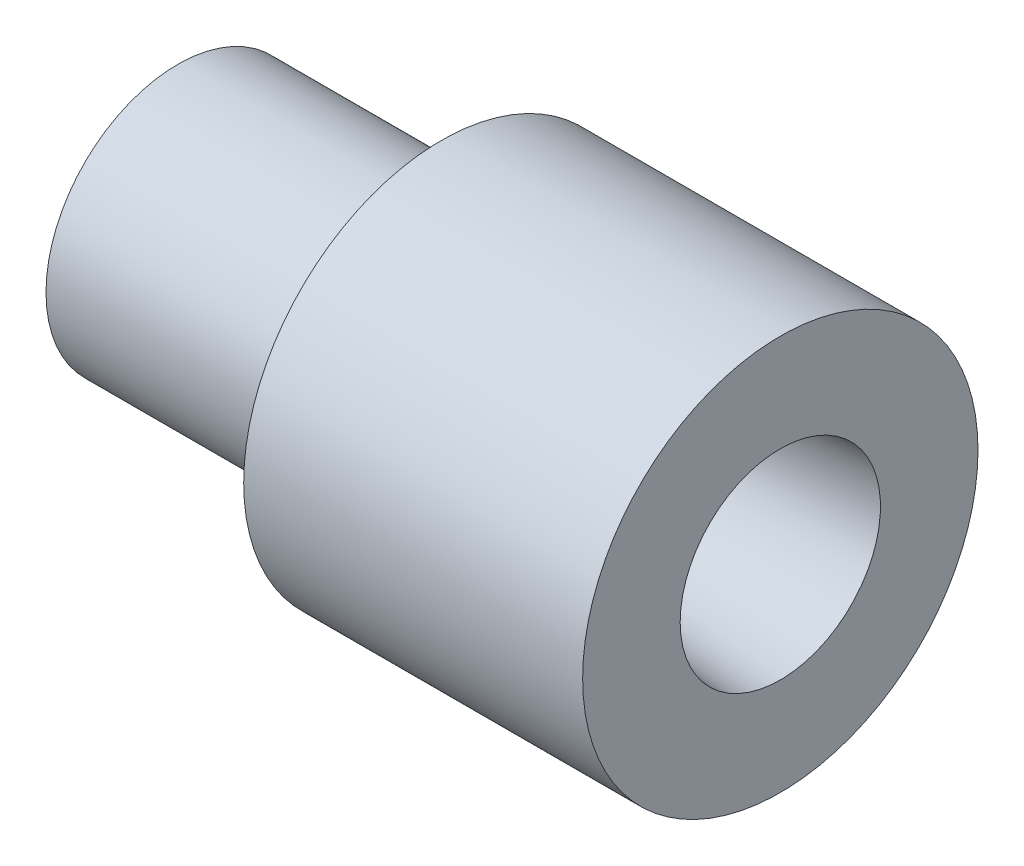
SolidWorks part; units mm, degrees
ref_plane "Front Plane" through (0, 0, 0) normal (0, 0, 1) x (1, 0, 0)
ref_plane "Top Plane" through (0, 0, 0) normal (0, 1, 0) x (1, 0, 0)
ref_plane "Right Plane" through (0, 0, 0) normal (1, 0, 0) x (0, 0, -1)
sketch "Sketch1" plane through (0, 0, 0) normal (0, 1, 0) x (1, 0, 0)
  line L0 (0, 0) -> (0, 2.286) construction
  line L1 (0, 2.286) -> (0, 6.35)
  line L2 (12.7, 9.525) -> (29.0323, 9.525)
  line L3 (29.0323, 9.525) -> (29.0323, 4.826)
  line L4 (29.0323, 4.826) -> (0, 2.286)
  line L5 (0, 0) -> (29.0323, 0) construction
  line L6 (29.0323, 0) -> (29.0323, 4.826) construction
  line L8 (12.7, 6.35) -> (12.7, 9.525)
  line L12 (0, 6.35) -> (12.7, 6.35)
  dimension "D1" = 2.286
  dimension "D2" = 4.826
  dimension "D3" = 5
  dimension "D4" = 9.525
  dimension "D5" = 6.35
  dimension "D6" = 12.7
revolve "Revolve1" add sketch "Sketch1" angle 360 about L5
equation "\"z\" = 8\t\t\t\t'number of blades"
equation "\"de\" = 0.43in\t\t\t'entrance eye diameter"
equation "\"de_length\" = 4mm\t\t'entrance eye consistent length"
equation "\"d_exit\" = 0.18in \t\t'throat aka d1"
equation "\"d2\" = 2.1in \t\t\t'outer diameter of the impeller"
equation "\"b2\" = .2in\t\t\t'tip height from disc surface at d2; slightly higher than d_exit"
equation "\"b1\" = \"b2\" + (\"d2\"/2 - \"de\"/2)*tan(\"theta\") \t\t\t'tip height from disc surface at inlet eye"
equation "\"theta\" = 12\t\t\t'angle of blades from inner to outer "
equation "\"ae\" = 3.14*(\"de\"^2)/4\t\t'entrance eye area'"
equation "\"ce\" = 3.14*\"de\"\t\t'entrance eye circumference"
equation "\"av_ratio\" = .325\t\t'ratio of av/ae at N_s of 470, range is .275 to .375, .325 ideal. High ratio means bigger area means smaller blades"
equation "\"av\" = \"ae\"*\"av_ratio\"\t\t'area between just two blades"
equation "\"s_open\" = \"av\"/\"b1\"\t\t'width of open area"
equation "\"s\"=\"ce\" - \"z\"*\"s_open\""
equation "\"min blade thickness\" = .15in"
equation "\"bearing OD\" = 30mm"
equation "\"bearing ID\"= 10mm"
equation "\"bearing depth\"= 9mm"
equation "\"bearing outer race thickness\"= 1mm"
equation "\"bearing inner race thickness\"= 1mm"
equation "\"bearing bore\" = \"bearing depth\" + 1mm"
equation "\"lower seal OD\" = .917in\t\t'this is https://www.mcmaster.com/#9281k121/=174001b"
equation "\"lower seal ID\"= .375in"
equation "\"lower seal depth\" = .625in + .218in"
equation "\"lower seal bore\" = \"lower seal depth\" + 1mm"
equation "\"upper seal OD\" = 1.125in\t'this is https://www.mcmaster.com/#5154t33/=173zuau, needs to be visually inspected before machining!"
equation "\"upper seal ID\"= 0.625in"
equation "\"upper seal depth\"= .25in\t'aka height; these values need to be confirmed by inspection!! We may want to compress the height."
equation "\"upper seal bore\" = \"upper seal depth\" + 1mm"
equation "\"big o-ring thickness\" = .139in"
equation "\"big o-ring OD\" = 2.734in"
equation "\"big o-ring ID\" = 3.012in"
equation "\"big o-ring groove depth\" = \"big o-ring thickness\"*4/5"
equation "\"impeller center height\" = \"impeller base thickness\" + \"b1\"\t'impeller height at de"
equation "\"impeller outer height\" = \"impeller base thickness\" + \"b2\"\t'impeller height at de"
equation "\"impeller upper clearance\"= .5mm"
equation "\"impeller horizontal clearance\"= (\"d2\"*1.15 - \"d2\")/2 \t\t'clearance based on D2-D3 ratio for circular volute, ranges 1.15 to 1.2"
equation "\"impeller bottom clearance\"= .5mm"
equation "\"impeller base thickness\"= 2mm"
equation "\"impeller dowel diameter\" = 2mm"
equation "\"impeller bolt head diameter\" = \"m4 head bore diameter\""
equation "\"impeller bolt head depth\" = 4mm"
equation "\"impeller bolt stop depth\" = 3mm"
equation "\"impeller bolt bore\" = \"m4 clearance\""
equation "\"impeller shaft bore depth\" = 12mm"
equation "\"impeller shaft bore\" = 8mm"
equation "\"impeller boss depth\" = \"impeller shaft bore depth\"+\"impeller bolt stop depth\"+\"impeller bolt head depth\"-\"impeller base thickness\""
equation "\"impeller boss diameter\" = \"upper seal ID\""
equation "\"impeller dowel length\" = 2mm*2 + \"impeller shaft bore\""
equation "\"coupler motor shaft hole ID\"= 8mm"
equation "\"coupler OD\"= 17mm"
equation "\"coupler length\"= 25mm"
equation "\"motor OD\" = 64mm"
equation "\"motor shaft diameter\"= 8mm"
equation "\"motor shaft pride\"= 32mm"
equation "\"motor to bearing plate distance\" = \"motor shaft pride\" + 2mm +\"coupler length\"/2"
equation "\"square plate bolt bore\" = \"m8 clearance\""
equation "\"square plate bolt head diameter\" = 13.5mm"
equation "\"square plate bolt head depth\" = 8mm"
equation "\"square plate bolt pattern diameter\"= 3.5in"
equation "\"motor mount center bore\"= \"coupler OD\"+ 4mm"
equation "\"motor mount post radius\"= ( 3 * \"square plate bolt bore\" ) / 2"
equation "\"motor mount m4 screw hole diameter\"= 4mm"
equation "\"motor mount m4 head diameter\"= 7.25mm"
equation "\"motor mount m4 head depth\"= 4mm"
equation "\"motor mount m4 pattern diamater\" = 30mm"
equation "\"motor mount plate thickness\"= 8mm + \"motor mount m4 head depth\""
equation "\"bearing plate stop ID\" = \"bearing OD\" - 4mm"
equation "\"bearing plate stop depth\" = 3mm"
equation "\"bearing plate thickness\" = \"bearing bore\" + \"bearing plate stop depth\" + \"shaft bearing stop length\""
equation "\"lower seal plate lip depth\" = 2mm"
equation "\"lower seal plate lip ID\" = \"lower seal OD\" - 3mm"
equation "\"lower seal plate thickness\" = \"lower seal plate lip depth\" + \"lower seal bore\""
equation "\"shaft coupler section diameter\" = 8mm"
equation "\"shaft coupler section length\" = \"motor to bearing plate distance\" - \"motor shaft pride\" - 2mm"
equation "\"shaft bearing section diameter\" = \"bearing ID\""
equation "\"shaft bearing section length\" = \"bearing plate stop depth\" + \"bearing depth\""
equation "\"shaft bearing stop diameter\" = \"bearing ID\" + 4mm"
equation "\"shaft bearing stop length\" = 3mm"
equation "\"shaft lower seal section diameter\" = \"lower seal ID\""
equation "\"shaft lower seal section length\" = \"lower seal plate thickness\" + 1mm"
equation "\"shaft impeller section diameter\" = \"impeller shaft bore\""
equation "\"shaft impeller section length\" = \"upper seal plate thickness\" + \"upper seal plate riser\" + \"impeller bottom clearance\" + \"impeller base thickness\" - \"impeller bolt head depth\" - \"impeller bolt stop depth\""
equation "\"upper seal plate thickness\" = \"upper seal plate pressure hole diameter\"+10mm"
equation "\"upper seal plate lip ID\" = \"upper seal OD\" - 3mm"
equation "\"upper seal plate riser\" = 6.59mm \t\t'this number needs to be read from the housing file"
equation "\"upper seal plate pressure hole diameter\" = .125in\t'this is 1/8 drill "
equation "\"upper seal plate pressure tap diameter\" = .328125in \t'this is 21/64 drill for a 1/8 ANPT tap"
equation "\"upper seal plate pressure tap grip\" = 5mm\t\t'this is the area around the tap so it doesn't crack"
equation "\"upper seal plate pressure tap depth\" = 12mm"
equation "\"impeller cavity center height\"= \"impeller bottom clearance\" + \"impeller upper clearance\" + \"impeller center height\""
equation "\"impeller cavity diameter\"= 2 * \"impeller horizontal clearance\" + \"d2\" \t\t\t\t\t\t\t\t\t'called D3 analytically"
equation "\"impeller cavity outer height\"= \"impeller bottom clearance\" + \"impeller upper clearance\" + \"impeller base thickness\" + \"b2\" \t\t'this is height at impeller diameter d2, not at d3"
equation "\"impeller housing thickness\"= \"impeller housing exit threaded diameter\" + 2*\"impeller housing outlet grip\""
equation "\"impeller housing diameter\" = 4.5in"
equation "\"impeller housing bolt count\" = 8"
equation "\"impeller housing bolt diameter\" = \"m6 clearance\""
equation "\"impeller housing bolt pattern diameter\" = 3.5in"
equation "\"impeller housing threaded inlet diameter\" = 0.71875in \t'this is the 23/32 drill size for 1/2 NPT fitting https://www.mcmaster.com/#50715k269/=176pljy"
equation "\"impeller housing threaded inlet depth\"= .6in"
equation "\"impeller housing exit threaded diameter\"= 0.515625in \t\t'this is the 33/64 drill size for 9/16-18 fitting, expecting swagelok SS-8FK0-1-6STH fitting"
equation "\"impeller housing exit threaded depth\"= 10mm"
equation "\"impeller housing diffuser conical angle\"=10"
equation "\"impeller housing diffuser tangent angle\"=5"
equation "\"impeller housing diffuser final diameter\" = .38in\t\t'aka d2'"
equation "\"impeller housing outlet grip\" = 5mm"
equation "\"end mill size\" = 0.375in\t'for 3/8 endmill"
equation "\"m4 clearance\" = 0.171875in \t'this is 11/64 bit for 4.36mm"
equation "\"m4 tap\" = 0.125in\t\t'this is 1/8 bit for 3.17mm"
equation "\"m4 head bore diameter\" = 7.5mm"
equation "\"m4 head bore depth\" = 5mm\t'actual is ~4mm"
equation "\"m6 clearance\" = 0.234375in\t'this is 15/64 bit = 5.95mm, could use 6mm bit, B bit for 6.04mm or 1/4 bit for 6.35mm"
equation "\"m6 tap\" = 5mm\t\t\t'5mm is appropriate, could use 13/64 or #5,6,7"
equation "\"m6 head bore diameter\" = 11mm\t\t"
equation "\"m6 head bore depth\" = 7mm\t'actual is 6mm"
equation "\"m8 clearance\" = 0.3125in\t'this is 5/16in for 7.93mm, could use 8mm, O,P, or 21/64"
equation "\"m8 tap\" = 0.265625in\t\t'this is 17/64 for 6.746875mm"
equation "\"m8 head bore diameter\" = 14mm"
equation "\"m8 head bore depth\" = 9mm\t'actual is 8mm"
equation "\"D1@Sketch1\"=\"d_exit\"/2"
equation "\"D2@Sketch1\"=\"impeller housing diffuser final diameter\"/2"
equation "\"diffuser cartridge OD\" =.75in"
equation "\"D4@Sketch1\"=\"diffuser cartridge OD\"/2"
